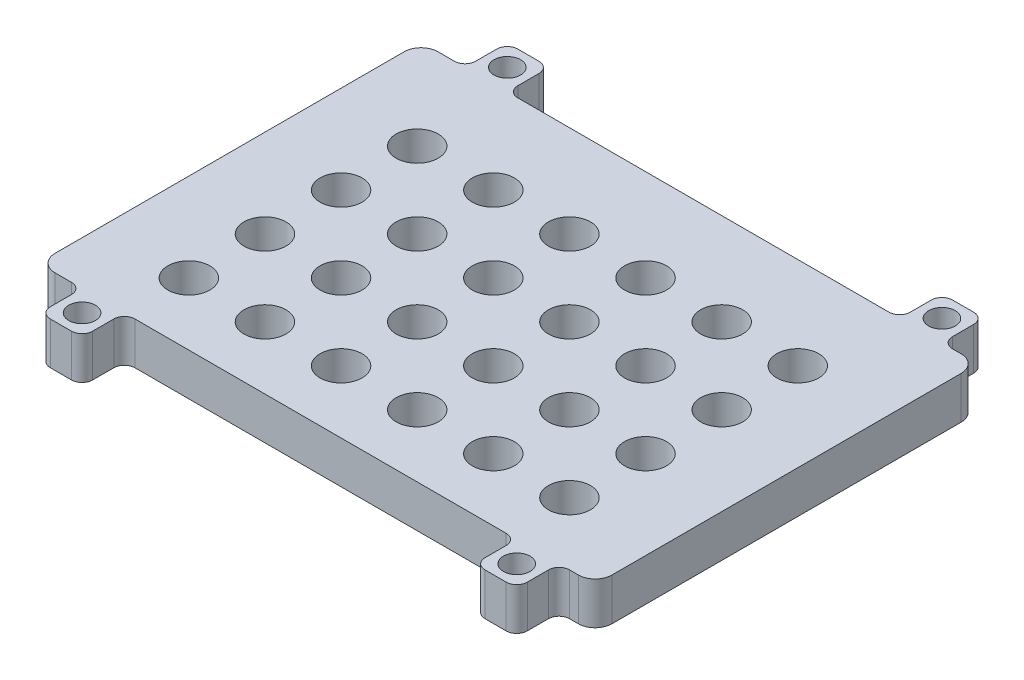
SolidWorks part; units mm, degrees
ref_plane "Front Plane" through (0, 0, 0) normal (0, 0, 1) x (1, 0, 0)
ref_plane "Top Plane" through (0, 0, 0) normal (0, 1, 0) x (1, 0, 0)
ref_plane "Right Plane" through (0, 0, 0) normal (1, 0, 0) x (0, 0, -1)
sketch "Sketch1" plane through (0, 0, 0) normal (0, 1, 0) x (1, 0, 0)
  line L0 (9, 23.5) -> (9, 45.2755) construction
  line L1 (65.8635, 45.2755) -> (-65.8635, 45.2755)
  line L2 (65.8635, 45.2755) -> (65.8635, -45.2755)
  line L3 (65.8635, -45.2755) -> (-65.8635, -45.2755)
  line L4 (-65.8635, 45.2755) -> (-65.8635, -45.2755)
  line L5 (65.8635, 45.2755) -> (-65.8635, -45.2755) construction
  line L6 (65.8635, -45.2755) -> (-65.8635, 45.2755) construction
  line L7 (-45, 23.5) -> (-65.8635, 23.5) construction
  line L8 (45, -30.5) -> (65.8635, -30.5) construction
  line L9 (45, -30.5) -> (45, -45.2755) construction
  circle A0 centre (-45, 23.5) radius 3.5
  circle A1 centre (-27, 23.5) radius 3.5
  circle A2 centre (-9, 23.5) radius 3.5
  circle A3 centre (9, 23.5) radius 3.5
  circle A4 centre (27, 23.5) radius 3.5
  circle A5 centre (45, 23.5) radius 3.5
  circle A6 centre (-27, 5.5) radius 3.5
  circle A7 centre (-9, 5.5) radius 3.5
  circle A8 centre (9, 5.5) radius 3.5
  circle A9 centre (27, 5.5) radius 3.5
  circle A10 centre (45, 5.5) radius 3.5
  circle A11 centre (-27, -12.5) radius 3.5
  circle A12 centre (-9, -12.5) radius 3.5
  circle A13 centre (9, -12.5) radius 3.5
  circle A14 centre (27, -12.5) radius 3.5
  circle A15 centre (45, -12.5) radius 3.5
  circle A16 centre (-27, -30.5) radius 3.5
  circle A17 centre (-9, -30.5) radius 3.5
  circle A18 centre (9, -30.5) radius 3.5
  circle A19 centre (27, -30.5) radius 3.5
  circle A20 centre (45, -30.5) radius 3.5
  circle A21 centre (-45, 5.5) radius 3.5
  circle A22 centre (-45, -12.5) radius 3.5
  circle A23 centre (-45, -30.5) radius 3.5
  point P0 (0, 0)
  dimension "D3" = 7
  dimension "D4" = 6
  dimension "D1" = 131.727
  dimension "D2" = 90.551
  dimension "D6" = 18
  dimension "D7" = 18
  dimension "D8" = 14.7755
  dimension "D5" = 4
extrude "Boss-Extrude1" add sketch "Sketch1" along normal blind 10
sketch "Sketch3" plane through (0, 0, 0) normal (0, -1, 0) x (1, 0, 0)
  line L0 (65.8635, -45.2755) -> (-65.8635, -45.2755) construction
  line L1 (47.3134, -45.2755) -> (57.3134, -45.2755)
  line L2 (47.3134, -45.2755) -> (47.3134, -55.2755)
  line L3 (47.3134, -55.2755) -> (57.3134, -55.2755)
  line L4 (57.3134, -45.2755) -> (57.3134, -55.2755)
  line L5 (-65.8635, 45.2755) -> (65.8635, 45.2755) construction
  line L6 (-45.4727, -45.2755) -> (-55.4727, -45.2755)
  line L7 (-45.4727, -45.2755) -> (-45.4727, -55.2755)
  line L8 (-45.4727, -55.2755) -> (-55.4727, -55.2755)
  line L9 (-55.4727, -45.2755) -> (-55.4727, -55.2755)
  line L10 (-55.4727, 45.2755) -> (-45.4727, 45.2755)
  line L11 (-55.4727, 45.2755) -> (-55.4727, 55.2755)
  line L12 (-55.4727, 55.2755) -> (-45.4727, 55.2755)
  line L13 (-45.4727, 45.2755) -> (-45.4727, 55.2755)
  line L14 (-55.4727, -45.2755) -> (-65.8635, -45.2755) construction
  line L15 (47.3134, 45.2755) -> (57.3134, 45.2755)
  line L16 (47.3134, 45.2755) -> (47.3134, 55.2755)
  line L17 (47.3134, 55.2755) -> (57.3134, 55.2755)
  line L18 (57.3134, 45.2755) -> (57.3134, 55.2755)
  line L19 (-55.4727, -55.2755) -> (-45.4727, -45.2755) construction
  line L20 (-55.4727, 55.2755) -> (-45.4727, 45.2755) construction
  line L21 (-55.4727, 45.2755) -> (-65.8635, 45.2755) construction
  line L22 (47.3134, 55.2755) -> (57.3134, 45.2755) construction
  line L23 (47.3134, -55.2755) -> (57.3134, -45.2755) construction
  point P20 (-50.4727, 50.2755)
  point P23 (-50.4727, -50.2755)
  point P24 (45, 30.5)
  point P29 (52.3134, 50.2755)
  point P31 (52.3134, -50.2755)
  dimension "D1" = 10
  dimension "D2" = 102.7861
  dimension "D3" = 102.7861
  dimension "D4" = 7.3134
  dimension "D5" = 7.3134
  dimension "D6" = 13.5501
  dimension "D7" = 15.3908
  dimension "D8" = 13.5501
  dimension "D9" = 15.3908
extrude "Boss-Extrude3" add sketch "Sketch3" against normal up to surface (10 mm away) up to face at (-45, 10, 16)
sketch "Sketch4" plane through (0, 0, 0) normal (0, -1, 0) x (-1, 0, 0)
  line L0 (-57.3134, 55.2755) -> (-47.3134, 45.2755) construction
  line L1 (55.4727, 55.2755) -> (45.4727, 45.2755) construction
  line L2 (-57.3134, -45.2755) -> (-47.3134, -55.2755) construction
  line L3 (55.4727, -45.2755) -> (45.4727, -55.2755) construction
  circle A0 centre (-52.3134, -50.2755) radius 3.15
  circle A1 centre (50.4727, -50.2755) radius 3.15
  circle A2 centre (50.4727, 50.2755) radius 3.15
  circle A3 centre (-52.3134, 50.2755) radius 3.15
  dimension "D1" = 6.3
extrude "Cut-Extrude2" cut sketch "Sketch4" against normal through all
fillet "Fillet2" radius 2.5 16 edges at (47.3134, 5, 55.2755) (47.3134, 5, 45.2755) (57.3134, 5, 55.2755) (57.3134, 5, 45.2755) (-45.4727, 5, 55.2755) (-55.4727, 5, 55.2755) (-45.4727, 5, -45.2755) (-45.4727, 5, -55.2755) (-55.4727, 5, -45.2755) (-55.4727, 5, -55.2755) (47.3134, 5, -55.2755) (57.3134, 5, -55.2755)
fillet "Fillet3" radius 4 4 edges at (-65.8635, 5, -45.2755) (-65.8635, 5, 45.2755) (65.8635, 5, 45.2755) (65.8635, 5, -45.2755)
sketch "Sketch5" plane through (0, 10, 0) normal (0, 1, 0) x (1, 0, 0)
  circle A0 centre (45, -30.5) radius 4.975
  circle A1 centre (27, -30.5) radius 4.975
  circle A2 centre (9, -30.5) radius 4.975
  circle A3 centre (-9, -30.5) radius 4.975
  circle A4 centre (-27, -30.5) radius 4.975
  circle A5 centre (-45, -30.5) radius 4.975
  circle A6 centre (45, -12.5) radius 4.975
  circle A7 centre (27, -12.5) radius 4.975
  circle A8 centre (9, -12.5) radius 4.975
  circle A9 centre (-9, -12.5) radius 4.975
  circle A10 centre (-27, -12.5) radius 4.975
  circle A11 centre (-45, -12.5) radius 4.975
  circle A12 centre (45, 5.5) radius 4.975
  circle A13 centre (27, 5.5) radius 4.975
  circle A14 centre (9, 5.5) radius 4.975
  circle A15 centre (-9, 5.5) radius 4.975
  circle A16 centre (-27, 5.5) radius 4.975
  circle A17 centre (-45, 5.5) radius 4.975
  circle A18 centre (45, 23.5) radius 4.975
  circle A19 centre (27, 23.5) radius 4.975
  circle A20 centre (9, 23.5) radius 4.975
  circle A21 centre (-9, 23.5) radius 4.975
  circle A22 centre (-27, 23.5) radius 4.975
  circle A23 centre (-45, 23.5) radius 4.975
  dimension "D1" = 9.95
extrude "Cut-Extrude3" cut sketch "Sketch5" against normal blind 9.5
